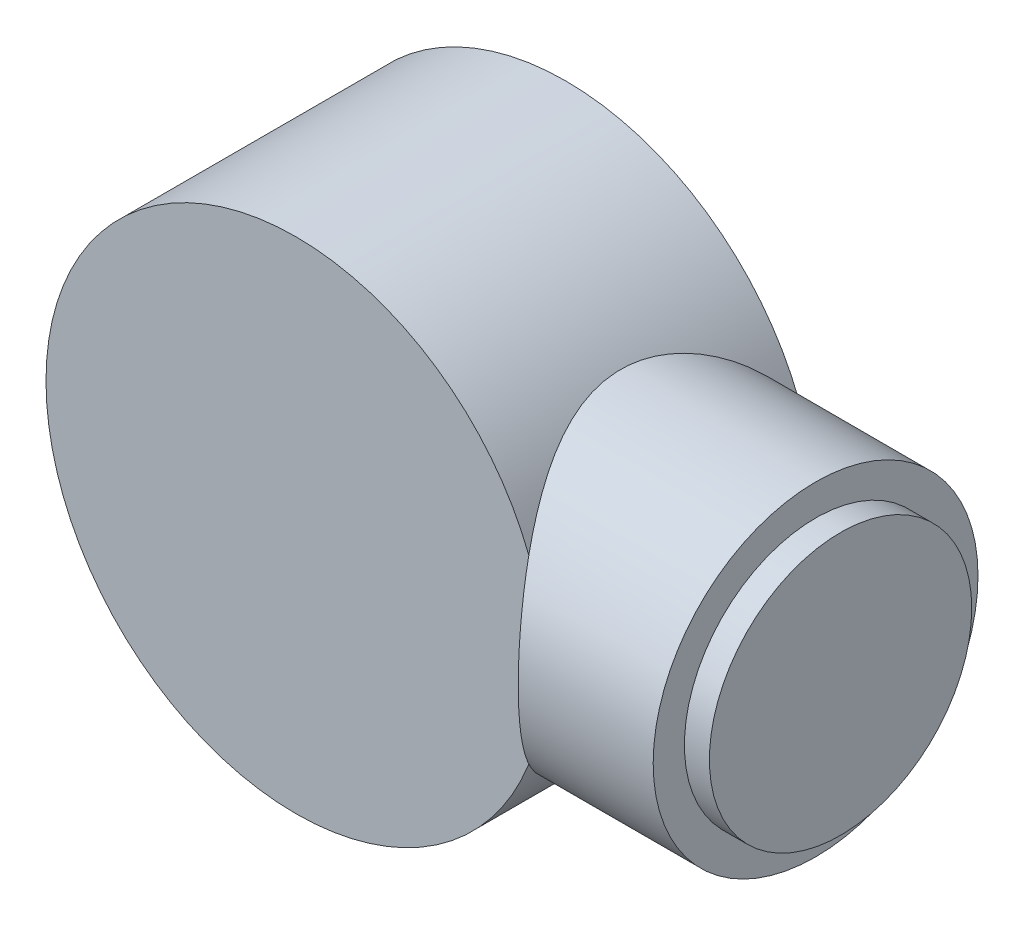
SolidWorks part; units mm, degrees
ref_plane "Front Plane" through (0, 0, 0) normal (0, 0, 1) x (1, 0, 0)
ref_plane "Top Plane" through (0, 0, 0) normal (0, 1, 0) x (1, 0, 0)
ref_plane "Right Plane" through (0, 0, 0) normal (1, 0, 0) x (0, 0, -1)
sketch "Sketch1" plane through (0, 0, 0) normal (0, 0, 1) x (1, 0, 0)
  circle A0 centre (0, 0) radius 50
  dimension "D1" = 100
extrude "Boss-Extrude1" add sketch "Sketch1" along normal blind 54
ref_plane "Plane1" through (77, 0, 0) normal (1, 0, 0) x (0, 0, -1)
sketch "Sketch2" plane through (77, 0, 0) normal (1, 0, 0) x (0, 0, -1)
  line L0 (0, 50) -> (-54, 50) construction
  line L1 (0, 50) -> (-54, 50)
  circle A0 centre (-27, 0) radius 32.5
  point P2 (0, 0)
  point P6 (-27, 50)
  dimension "D1" = 65
extrude "Boss-Extrude2" add sketch "Sketch2" against normal up to surface (27 mm away) separate body contours A0 up to face at (50, 0, 54)
sketch "Sketch3" plane through (77, 0, 0) normal (1, 0, 0) x (0, 0, -1)
  circle A0 centre (-27, 0) radius 26.25
  dimension "D1" = 52.5
extrude "Boss-Extrude3" add sketch "Sketch3" along normal blind 5
